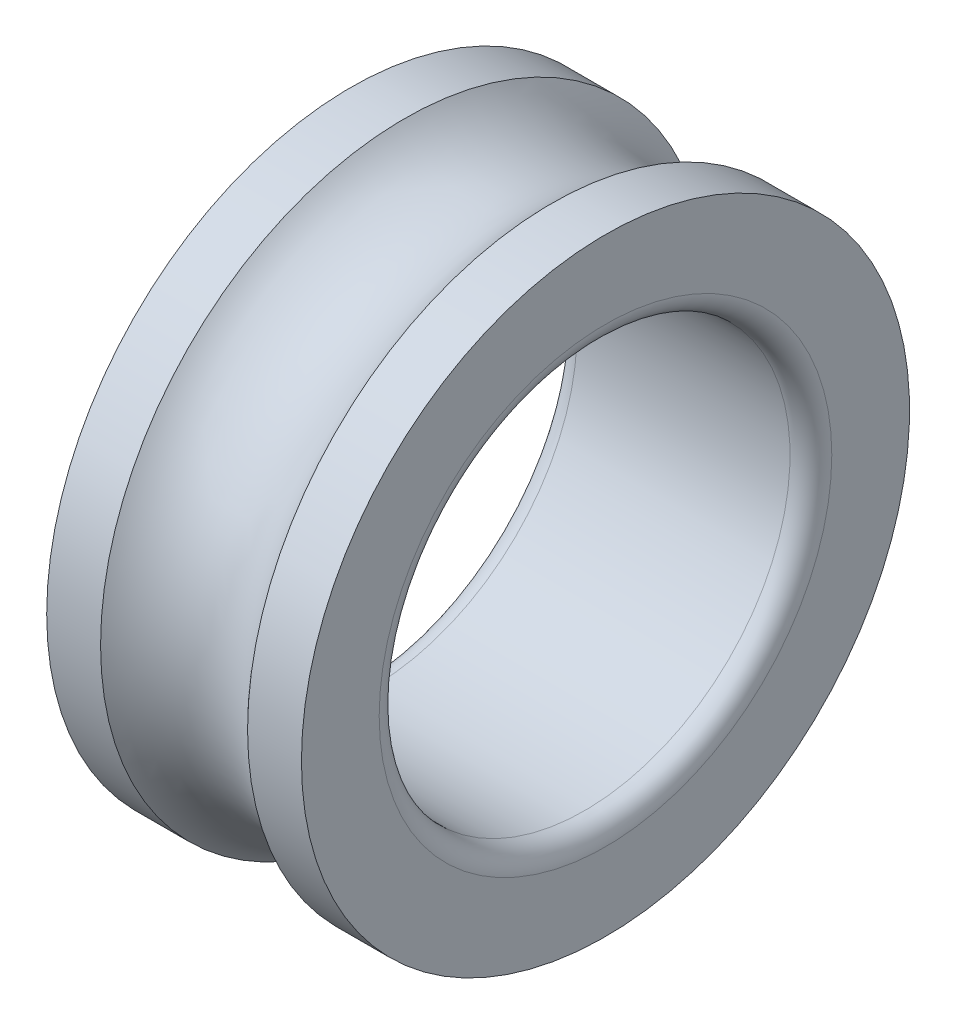
SolidWorks part; units mm, degrees
ref_plane "Front Plane" through (0, 0, 0) normal (0, 0, 1) x (1, 0, 0)
ref_plane "Top Plane" through (0, 0, 0) normal (0, 1, 0) x (1, 0, 0)
ref_plane "Right Plane" through (0, 0, 0) normal (1, 0, 0) x (0, 0, -1)
sketch "Sketch1" plane through (0, 0, 0) normal (0, 0, 1) x (1, 0, 0)
  line L0 (-21.6667, 0) -> (44, 0) construction
  line L1 (0, 25) -> (0, 0) construction
  line L2 (-15.5, 37) -> (-8.9443, 37)
  line L3 (-15.5, 37) -> (-15.5, 27.54)
  line L4 (-12.96, 25) -> (12.96, 25)
  line L5 (15.5, 37) -> (15.5, 27.54)
  line L6 (-15.5, 37) -> (15.5, 25) construction
  line L7 (-15.5, 25) -> (15.5, 37) construction
  line L8 (8.9443, 37) -> (15.5, 37)
  arc A0 (8.9443, 37) -> (-8.9443, 37) centre (0, 45) cw
  arc A1 (-15.5, 27.54) -> (-12.96, 25) centre (-12.96, 27.54) ccw
  arc A2 (12.96, 25) -> (15.5, 27.54) centre (12.96, 27.54) ccw
  point P3 (0, 31)
  dimension "D5" = 12
  dimension "D6" = 2.54
  dimension "D1" = 31
  dimension "D2" = 25
  dimension "D3" = 37
  dimension "D4" = 8
  dimension "D7" = 25
revolve "Revolve1" add sketch "Sketch1" angle 360 about L0
scale "Scale1" scale about centroid uniform scaling yes scale factor 0.35
